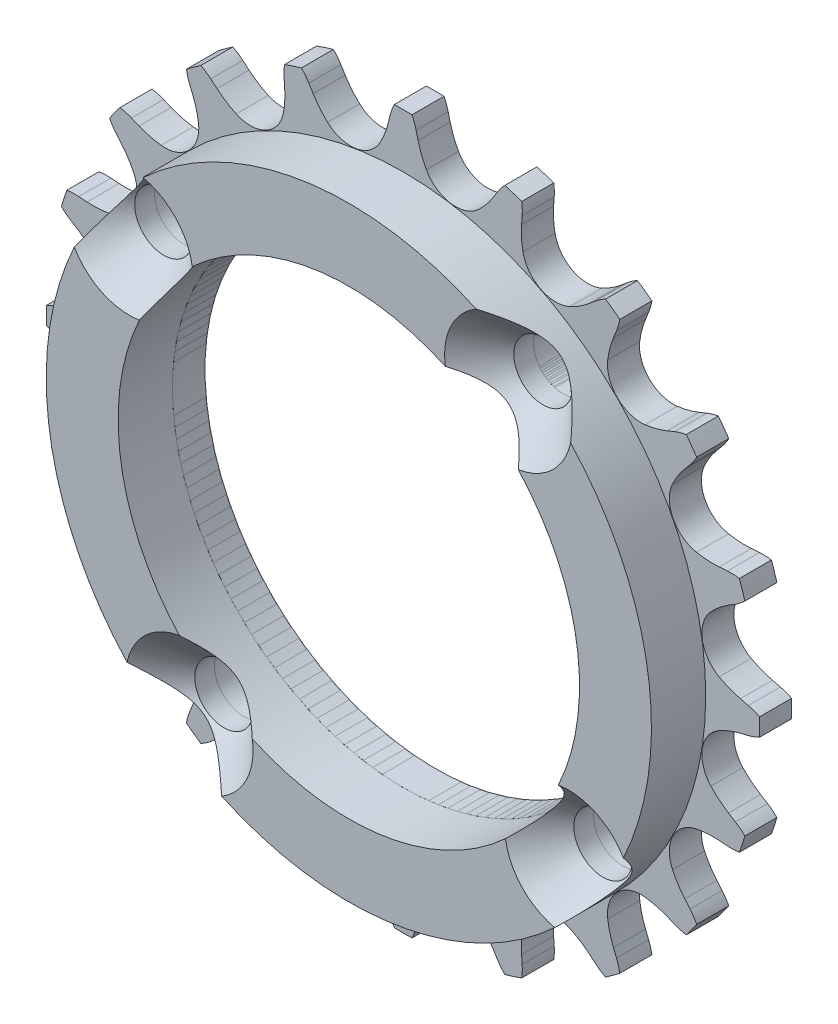
SolidWorks part; units mm, degrees
ref_plane "Front" through (0, 0, 0) normal (0, 0, 1) x (1, 0, 0)
ref_plane "Top" through (0, 0, 0) normal (0, 1, 0) x (1, 0, 0)
ref_plane "Right" through (0, 0, 0) normal (1, 0, 0) x (0, 0, -1)
sketch "Sketch1" plane through (0, 0, 0.25) normal (0, 0, 1) x (1, 0, 0)
  line L0 (-24.4882, 6.9486) -> (-23.9765, 6.6313)
  line L1 (-24.8522, 1.1024) -> (-25.4369, 0.9588)
  line L2 (-25.4369, -0.9588) -> (-24.8522, -1.1024)
  line L3 (-23.9765, -6.6313) -> (-24.4882, -6.9486)
  line L4 (-23.8957, -8.7723) -> (-23.2952, -8.7282)
  line L5 (-20.7538, -13.7159) -> (-21.1425, -14.1758)
  line L6 (-20.0154, -15.7271) -> (-19.4579, -15.4996)
  line L7 (-15.4996, -19.4579) -> (-15.7271, -20.0154)
  line L8 (-14.1758, -21.1425) -> (-13.7159, -20.7538)
  line L9 (-8.7282, -23.2952) -> (-8.7723, -23.8957)
  line L10 (-6.9486, -24.4882) -> (-6.6313, -23.9765)
  line L11 (-1.1024, -24.8522) -> (-0.9588, -25.4369)
  line L12 (0.9588, -25.4369) -> (1.1024, -24.8522)
  line L13 (6.6313, -23.9765) -> (6.9486, -24.4882)
  line L14 (8.7723, -23.8957) -> (8.7282, -23.2952)
  line L15 (13.7159, -20.7538) -> (14.1758, -21.1425)
  line L16 (15.7271, -20.0154) -> (15.4996, -19.4579)
  line L17 (19.4579, -15.4996) -> (20.0154, -15.7271)
  line L18 (21.1425, -14.1758) -> (20.7538, -13.7159)
  line L19 (23.2952, -8.7282) -> (23.8957, -8.7723)
  line L20 (24.4882, -6.9486) -> (23.9765, -6.6313)
  line L21 (24.8522, -1.1024) -> (25.4369, -0.9588)
  line L22 (25.4369, 0.9588) -> (24.8522, 1.1024)
  line L23 (23.9765, 6.6313) -> (24.4882, 6.9486)
  line L24 (23.8957, 8.7723) -> (23.2952, 8.7282)
  line L25 (20.7538, 13.7159) -> (21.1425, 14.1758)
  line L26 (20.0154, 15.7271) -> (19.4579, 15.4996)
  line L27 (15.4996, 19.4579) -> (15.7271, 20.0154)
  line L28 (14.1758, 21.1425) -> (13.7159, 20.7538)
  line L29 (8.7282, 23.2952) -> (8.7723, 23.8957)
  line L30 (6.9486, 24.4882) -> (6.6313, 23.9765)
  line L31 (1.1024, 24.8522) -> (0.9588, 25.4369)
  line L32 (-0.9588, 25.4369) -> (-1.1024, 24.8522)
  line L33 (-6.6313, 23.9765) -> (-6.9486, 24.4882)
  line L34 (-8.7723, 23.8957) -> (-8.7282, 23.2952)
  line L35 (-13.7159, 20.7538) -> (-14.1758, 21.1425)
  line L36 (-15.7271, 20.0154) -> (-15.4996, 19.4579)
  line L37 (-19.4579, 15.4996) -> (-20.0154, 15.7271)
  line L38 (-21.1425, 14.1758) -> (-20.7538, 13.7159)
  line L39 (-23.2952, 8.7282) -> (-23.8957, 8.7723)
  line L40 (6.3855, 9.1279) -> (6.856, 9.5984)
  line L41 (9.5984, 6.856) -> (9.1279, 6.3855)
  line L42 (9.1279, -6.3855) -> (9.5984, -6.856)
  line L43 (6.856, -9.5984) -> (6.3855, -9.1279)
  line L44 (-6.3855, -9.1279) -> (-6.856, -9.5984)
  line L45 (-9.5984, -6.856) -> (-9.1279, -6.3855)
  line L46 (1.9392, 15.5134) -> (1.9392, 10.9696)
  line L47 (-1.9392, 10.9696) -> (-1.9392, 15.5134)
  line L48 (-1.9392, -15.5134) -> (-1.9392, -10.9696)
  line L49 (1.9392, -10.9696) -> (1.9392, -15.5134)
  line L50 (15.5134, -1.9392) -> (10.9696, -1.9392)
  line L51 (10.9696, 1.9392) -> (15.5134, 1.9392)
  line L52 (-15.5134, 1.9392) -> (-10.9696, 1.9392)
  line L53 (-10.9696, -1.9392) -> (-15.5134, -1.9392)
  line L54 (-6.856, 9.5984) -> (-6.3855, 9.1279)
  line L55 (-9.1279, 6.3855) -> (-9.5984, 6.856)
  arc A0 (-25.184, 7.4957) -> (-24.4882, 6.9486) centre (-22.3896, 10.3333) ccw
  arc A1 (-23.9765, 6.6313) -> (-22.6783, 5.565) centre (-27.3234, 1.2333) cw
  arc A2 (-22.6783, 5.565) -> (-23.288, 1.7154) centre (-24.487, 3.8784) cw
  arc A3 (-23.288, 1.7154) -> (-24.8522, 1.1024) centre (-26.3672, 7.2704) cw
  arc A4 (-25.4369, 0.9588) -> (-26.2677, 0.6534) centre (-24.487, -2.9088) ccw
  arc A5 (-26.2677, 0.6534) -> (-26.2677, -0.6534) centre (0, 0) ccw
  arc A6 (-26.2677, -0.6534) -> (-25.4369, -0.9588) centre (-24.487, 2.9088) ccw
  arc A7 (-24.8522, -1.1024) -> (-23.288, -1.7154) centre (-26.3672, -7.2704) cw
  arc A8 (-23.288, -1.7154) -> (-22.6783, -5.565) centre (-24.487, -3.8784) cw
  arc A9 (-22.6783, -5.565) -> (-23.9765, -6.6313) centre (-27.3234, -1.2333) cw
  arc A10 (-24.4882, -6.9486) -> (-25.184, -7.4957) centre (-22.3896, -10.3333) ccw
  arc A11 (-25.184, -7.4957) -> (-24.7802, -8.7386) centre (0, 0) ccw
  arc A12 (-24.7802, -8.7386) -> (-23.8957, -8.7723) centre (-24.1873, -4.8005) ccw
  arc A13 (-23.2952, -8.7282) -> (-21.6181, -8.8278) centre (-22.83, -15.0625) cw
  arc A14 (-21.6181, -8.8278) -> (-19.8487, -12.3006) centre (-22.09, -11.2554) cw
  arc A15 (-19.8487, -12.3006) -> (-20.7538, -13.7159) centre (-25.605, -9.6164) cw
  arc A16 (-21.1425, -14.1758) -> (-21.6351, -14.9112) centre (-18.1006, -16.7463) ccw
  arc A17 (-21.6351, -14.9112) -> (-20.867, -15.9684) centre (0, 0) ccw
  arc A18 (-20.867, -15.9684) -> (-20.0154, -15.7271) centre (-21.5201, -12.0398) ccw
  arc A19 (-19.4579, -15.4996) -> (-17.8321, -15.0761) centre (-17.0581, -21.3802) cw
  arc A20 (-17.8321, -15.0761) -> (-15.0761, -17.8321) centre (-17.5307, -17.5307) cw
  arc A21 (-15.0761, -17.8321) -> (-15.4996, -19.4579) centre (-21.3802, -17.0581) cw
  arc A22 (-15.7271, -20.0154) -> (-15.9684, -20.867) centre (-12.0398, -21.5201) ccw
  arc A23 (-15.9684, -20.867) -> (-14.9112, -21.6351) centre (0, 0) ccw
  arc A24 (-14.9112, -21.6351) -> (-14.1758, -21.1425) centre (-16.7463, -18.1006) ccw
  arc A25 (-13.7159, -20.7538) -> (-12.3006, -19.8487) centre (-9.6164, -25.605) cw
  arc A26 (-12.3006, -19.8487) -> (-8.8278, -21.6181) centre (-11.2554, -22.09) cw
  arc A27 (-8.8278, -21.6181) -> (-8.7282, -23.2952) centre (-15.0625, -22.83) cw
  arc A28 (-8.7723, -23.8957) -> (-8.7386, -24.7802) centre (-4.8005, -24.1873) ccw
  arc A29 (-8.7386, -24.7802) -> (-7.4957, -25.184) centre (0, 0) ccw
  arc A30 (-7.4957, -25.184) -> (-6.9486, -24.4882) centre (-10.3333, -22.3896) ccw
  arc A31 (-6.6313, -23.9765) -> (-5.565, -22.6783) centre (-1.2333, -27.3234) cw
  arc A32 (-5.565, -22.6783) -> (-1.7154, -23.288) centre (-3.8784, -24.487) cw
  arc A33 (-1.7154, -23.288) -> (-1.1024, -24.8522) centre (-7.2704, -26.3672) cw
  arc A34 (-0.9588, -25.4369) -> (-0.6534, -26.2677) centre (2.9088, -24.487) ccw
  arc A35 (-0.6534, -26.2677) -> (0.6534, -26.2677) centre (0, 0) ccw
  arc A36 (0.6534, -26.2677) -> (0.9588, -25.4369) centre (-2.9088, -24.487) ccw
  arc A37 (1.1024, -24.8522) -> (1.7154, -23.288) centre (7.2704, -26.3672) cw
  arc A38 (1.7154, -23.288) -> (5.565, -22.6783) centre (3.8784, -24.487) cw
  arc A39 (5.565, -22.6783) -> (6.6313, -23.9765) centre (1.2333, -27.3234) cw
  arc A40 (6.9486, -24.4882) -> (7.4957, -25.184) centre (10.3333, -22.3896) ccw
  arc A41 (7.4957, -25.184) -> (8.7386, -24.7802) centre (0, 0) ccw
  arc A42 (8.7386, -24.7802) -> (8.7723, -23.8957) centre (4.8005, -24.1873) ccw
  arc A43 (8.7282, -23.2952) -> (8.8278, -21.6181) centre (15.0625, -22.83) cw
  arc A44 (8.8278, -21.6181) -> (12.3006, -19.8487) centre (11.2554, -22.09) cw
  arc A45 (12.3006, -19.8487) -> (13.7159, -20.7538) centre (9.6164, -25.605) cw
  arc A46 (14.1758, -21.1425) -> (14.9112, -21.6351) centre (16.7463, -18.1006) ccw
  arc A47 (14.9112, -21.6351) -> (15.9684, -20.867) centre (0, 0) ccw
  arc A48 (15.9684, -20.867) -> (15.7271, -20.0154) centre (12.0398, -21.5201) ccw
  arc A49 (15.4996, -19.4579) -> (15.0761, -17.8321) centre (21.3802, -17.0581) cw
  arc A50 (15.0761, -17.8321) -> (17.8321, -15.0761) centre (17.5307, -17.5307) cw
  arc A51 (17.8321, -15.0761) -> (19.4579, -15.4996) centre (17.0581, -21.3802) cw
  arc A52 (20.0154, -15.7271) -> (20.867, -15.9684) centre (21.5201, -12.0398) ccw
  arc A53 (20.867, -15.9684) -> (21.6351, -14.9112) centre (0, 0) ccw
  arc A54 (21.6351, -14.9112) -> (21.1425, -14.1758) centre (18.1006, -16.7463) ccw
  arc A55 (20.7538, -13.7159) -> (19.8487, -12.3006) centre (25.605, -9.6164) cw
  arc A56 (19.8487, -12.3006) -> (21.6181, -8.8278) centre (22.09, -11.2554) cw
  arc A57 (21.6181, -8.8278) -> (23.2952, -8.7282) centre (22.83, -15.0625) cw
  arc A58 (23.8957, -8.7723) -> (24.7802, -8.7386) centre (24.1873, -4.8005) ccw
  arc A59 (24.7802, -8.7386) -> (25.184, -7.4957) centre (0, 0) ccw
  arc A60 (25.184, -7.4957) -> (24.4882, -6.9486) centre (22.3896, -10.3333) ccw
  arc A61 (23.9765, -6.6313) -> (22.6783, -5.565) centre (27.3234, -1.2333) cw
  arc A62 (22.6783, -5.565) -> (23.288, -1.7154) centre (24.487, -3.8784) cw
  arc A63 (23.288, -1.7154) -> (24.8522, -1.1024) centre (26.3672, -7.2704) cw
  arc A64 (25.4369, -0.9588) -> (26.2677, -0.6534) centre (24.487, 2.9088) ccw
  arc A65 (26.2677, -0.6534) -> (26.2677, 0.6534) centre (0, 0) ccw
  arc A66 (26.2677, 0.6534) -> (25.4369, 0.9588) centre (24.487, -2.9088) ccw
  arc A67 (24.8522, 1.1024) -> (23.288, 1.7154) centre (26.3672, 7.2704) cw
  arc A68 (23.288, 1.7154) -> (22.6783, 5.565) centre (24.487, 3.8784) cw
  arc A69 (22.6783, 5.565) -> (23.9765, 6.6313) centre (27.3234, 1.2333) cw
  arc A70 (24.4882, 6.9486) -> (25.184, 7.4957) centre (22.3896, 10.3333) ccw
  arc A71 (25.184, 7.4957) -> (24.7802, 8.7386) centre (0, 0) ccw
  arc A72 (24.7802, 8.7386) -> (23.8957, 8.7723) centre (24.1873, 4.8005) ccw
  arc A73 (23.2952, 8.7282) -> (21.6181, 8.8278) centre (22.83, 15.0625) cw
  arc A74 (21.6181, 8.8278) -> (19.8487, 12.3006) centre (22.09, 11.2554) cw
  arc A75 (19.8487, 12.3006) -> (20.7538, 13.7159) centre (25.605, 9.6164) cw
  arc A76 (21.1425, 14.1758) -> (21.6351, 14.9112) centre (18.1006, 16.7463) ccw
  arc A77 (21.6351, 14.9112) -> (20.867, 15.9684) centre (0, 0) ccw
  arc A78 (20.867, 15.9684) -> (20.0154, 15.7271) centre (21.5201, 12.0398) ccw
  arc A79 (19.4579, 15.4996) -> (17.8321, 15.0761) centre (17.0581, 21.3802) cw
  arc A80 (17.8321, 15.0761) -> (15.0761, 17.8321) centre (17.5307, 17.5307) cw
  arc A81 (15.0761, 17.8321) -> (15.4996, 19.4579) centre (21.3802, 17.0581) cw
  arc A82 (15.7271, 20.0154) -> (15.9684, 20.867) centre (12.0398, 21.5201) ccw
  arc A83 (15.9684, 20.867) -> (14.9112, 21.6351) centre (0, 0) ccw
  arc A84 (14.9112, 21.6351) -> (14.1758, 21.1425) centre (16.7463, 18.1006) ccw
  arc A85 (13.7159, 20.7538) -> (12.3006, 19.8487) centre (9.6164, 25.605) cw
  arc A86 (12.3006, 19.8487) -> (8.8278, 21.6181) centre (11.2554, 22.09) cw
  arc A87 (8.8278, 21.6181) -> (8.7282, 23.2952) centre (15.0625, 22.83) cw
  arc A88 (8.7723, 23.8957) -> (8.7386, 24.7802) centre (4.8005, 24.1873) ccw
  arc A89 (8.7386, 24.7802) -> (7.4957, 25.184) centre (0, 0) ccw
  arc A90 (7.4957, 25.184) -> (6.9486, 24.4882) centre (10.3333, 22.3896) ccw
  arc A91 (6.6313, 23.9765) -> (5.565, 22.6783) centre (1.2333, 27.3234) cw
  arc A92 (5.565, 22.6783) -> (1.7154, 23.288) centre (3.8784, 24.487) cw
  arc A93 (1.7154, 23.288) -> (1.1024, 24.8522) centre (7.2704, 26.3672) cw
  arc A94 (0.9588, 25.4369) -> (0.6534, 26.2677) centre (-2.9088, 24.487) ccw
  arc A95 (0.6534, 26.2677) -> (-0.6534, 26.2677) centre (0, 0) ccw
  arc A96 (-0.6534, 26.2677) -> (-0.9588, 25.4369) centre (2.9088, 24.487) ccw
  arc A97 (-1.1024, 24.8522) -> (-1.7154, 23.288) centre (-7.2704, 26.3672) cw
  arc A98 (-1.7154, 23.288) -> (-5.565, 22.6783) centre (-3.8784, 24.487) cw
  arc A99 (-5.565, 22.6783) -> (-6.6313, 23.9765) centre (-1.2333, 27.3234) cw
  arc A100 (-6.9486, 24.4882) -> (-7.4957, 25.184) centre (-10.3333, 22.3896) ccw
  arc A101 (-7.4957, 25.184) -> (-8.7386, 24.7802) centre (0, 0) ccw
  arc A102 (-8.7386, 24.7802) -> (-8.7723, 23.8957) centre (-4.8005, 24.1873) ccw
  arc A103 (-8.7282, 23.2952) -> (-8.8278, 21.6181) centre (-15.0625, 22.83) cw
  arc A104 (-8.8278, 21.6181) -> (-12.3006, 19.8487) centre (-11.2554, 22.09) cw
  arc A105 (-12.3006, 19.8487) -> (-13.7159, 20.7538) centre (-9.6164, 25.605) cw
  arc A106 (-14.1758, 21.1425) -> (-14.9112, 21.6351) centre (-16.7463, 18.1006) ccw
  arc A107 (-14.9112, 21.6351) -> (-15.9684, 20.867) centre (0, 0) ccw
  arc A108 (-15.9684, 20.867) -> (-15.7271, 20.0154) centre (-12.0398, 21.5201) ccw
  arc A109 (-15.4996, 19.4579) -> (-15.0761, 17.8321) centre (-21.3802, 17.0581) cw
  arc A110 (-15.0761, 17.8321) -> (-17.8321, 15.0761) centre (-17.5307, 17.5307) cw
  arc A111 (-17.8321, 15.0761) -> (-19.4579, 15.4996) centre (-17.0581, 21.3802) cw
  arc A112 (-20.0154, 15.7271) -> (-20.867, 15.9684) centre (-21.5201, 12.0398) ccw
  arc A113 (-20.867, 15.9684) -> (-21.6351, 14.9112) centre (0, 0) ccw
  arc A114 (-21.6351, 14.9112) -> (-21.1425, 14.1758) centre (-18.1006, 16.7463) ccw
  arc A115 (-20.7538, 13.7159) -> (-19.8487, 12.3006) centre (-25.605, 9.6164) cw
  arc A116 (-19.8487, 12.3006) -> (-21.6181, 8.8278) centre (-22.09, 11.2554) cw
  arc A117 (-21.6181, 8.8278) -> (-23.2952, 8.7282) centre (-22.83, 15.0625) cw
  arc A118 (-23.8957, 8.7723) -> (-24.7802, 8.7386) centre (-24.1873, 4.8005) ccw
  arc A119 (-24.7802, 8.7386) -> (-25.184, 7.4957) centre (0, 0) ccw
  circle A120 centre (0, 0) radius 6.7871
  arc A121 (9.1279, 6.3855) -> (6.3855, 9.1279) centre (7.7567, 7.7567) cw
  arc A122 (6.856, 9.5984) -> (9.5984, 6.856) centre (8.2272, 8.2272) cw
  arc A123 (6.3855, -9.1279) -> (9.1279, -6.3855) centre (7.7567, -7.7567) cw
  arc A124 (9.5984, -6.856) -> (6.856, -9.5984) centre (8.2272, -8.2272) cw
  arc A125 (-9.1279, -6.3855) -> (-6.3855, -9.1279) centre (-7.7567, -7.7567) cw
  arc A126 (-6.856, -9.5984) -> (-9.5984, -6.856) centre (-8.2272, -8.2272) cw
  arc A127 (1.9392, 10.9696) -> (-1.9392, 10.9696) centre (0, 10.9696) cw
  arc A128 (-1.9392, 15.5134) -> (1.9392, 15.5134) centre (0, 15.5134) cw
  arc A129 (-1.9392, -10.9696) -> (1.9392, -10.9696) centre (0, -10.9696) cw
  arc A130 (1.9392, -15.5134) -> (-1.9392, -15.5134) centre (0, -15.5134) cw
  arc A131 (10.9696, -1.9392) -> (10.9696, 1.9392) centre (10.9696, 0) cw
  arc A132 (15.5134, 1.9392) -> (15.5134, -1.9392) centre (15.5134, 0) cw
  arc A133 (-10.9696, 1.9392) -> (-10.9696, -1.9392) centre (-10.9696, 0) cw
  arc A134 (-15.5134, -1.9392) -> (-15.5134, 1.9392) centre (-15.5134, 0) cw
  arc A135 (-6.3855, 9.1279) -> (-9.1279, 6.3855) centre (-7.7567, 7.7567) cw
  arc A136 (-9.5984, 6.856) -> (-6.856, 9.5984) centre (-8.2272, 8.2272) cw
extrude "Boss-Extrude1" add sketch "Sketch1" against normal blind 2.3622
sketch "Sketch2" plane through (0, 0, 0.25) normal (0, 0, 1) x (1, 0, 0)
  circle A0 centre (0, 0) radius 18
extrude "Boss-Extrude2" add sketch "Sketch2" against normal blind 2.4 separate body
sketch "Sketch3" plane through (0, 0, 0.25) normal (0, 0, 1) x (1, 0, 0)
  circle A0 centre (0, 0) radius 17
extrude "Cut-Extrude1" cut sketch "Sketch3" against normal blind 2.4
sketch "Sketch6" plane through (0, 0, 0.25) normal (0, 0, 1) x (1, 0, 0)
  circle A0 centre (0, 0) radius 17
  circle A1 centre (0, 0) radius 22.3005
extrude "Boss-Extrude3" add sketch "Sketch6" along normal blind 4 separate body
sketch "Sketch5" plane through (0, 0, -2.1122) normal (0, 0, -1) x (-1, 0, 0)
  line L0 (21.2576, 15.4446) -> (13.7533, 9.9923)
  arc A0 (21.6351, 14.9112) -> (20.867, 15.9684) centre (0, 0) ccw construction
  circle A1 centre (0, 0) radius 17 construction
  circle A2 centre (16.1803, 11.7557) radius 2
  circle A3 centre (16.1803, 11.7557) radius 3
  circle A4 centre (11.7557, -16.1803) radius 2
  circle A5 centre (-16.1803, -11.7557) radius 2
  circle A6 centre (-11.7557, 16.1803) radius 2
  point P20 (0, 0)
  dimension "D1" = 3
  dimension "D2" = 4
extrude "Cut-Extrude3" cut sketch "Sketch5" against normal through all contours L0 A2 | L0 A2 | A4 | A5 | A6
hole_wizard "CSK for M4 Countersunk Flat Head Screw1" positions "3DSketch1" profile "Sketch8" countersink size "M4" standard "DIN"
sketch3d "3DSketch1"
  line L0 (-11.7557, -16.1803, 4.25) -> (-11.7557, -16.1803, 0.25) construction
  line L1 (16.1803, -11.7557, 4.25) -> (16.1803, -11.7557, 0.25) construction
  line L2 (11.7557, 16.1803, 4.25) -> (11.7557, 16.1803, 0.25) construction
  line L3 (-16.1803, 11.7557, 4.25) -> (-16.1803, 11.7557, 0.25) construction
  circle A0 centre (-11.7557, -16.1803, 4.25) radius 2 construction
  point P0 (-10.2992, -17.551, 4.25)
  point P4 (-11.7557, -16.1803, 2.25)
  point P5 (-11.7557, -16.1803, 4.25)
  point P9 (16.1803, -11.7557, 4.25)
  point P13 (11.7557, 16.1803, 4.25)
  point P17 (-16.1803, 11.7557, 4.25)
sketch "Sketch8" plane through (-16.1803, 11.7557, 4.25) normal (1, 0, 0) x (0, -1, 0)
  line L0 (0, 0) -> (0, 6.4)
  line L1 (0, 6.4) -> (2.15, 6.4)
  line L2 (2.15, 6.4) -> (2.15, 2.55)
  line L3 (2.15, 2.55) -> (4.7, 0)
  line L5 (4.7, 0) -> (0, 0)
  line L6 (-2.15, 2.55) -> (-4.7, 0) construction
  line L11 (0, -6.35) -> (0, 107.95) construction
  dimension "Thru Hole Dia." = 4.3
  dimension "Thru Hole Depth" = 6.4
  dimension "Near C'Sink Dia." = 9.4
  dimension "Near C'Sink Angle" = 90
